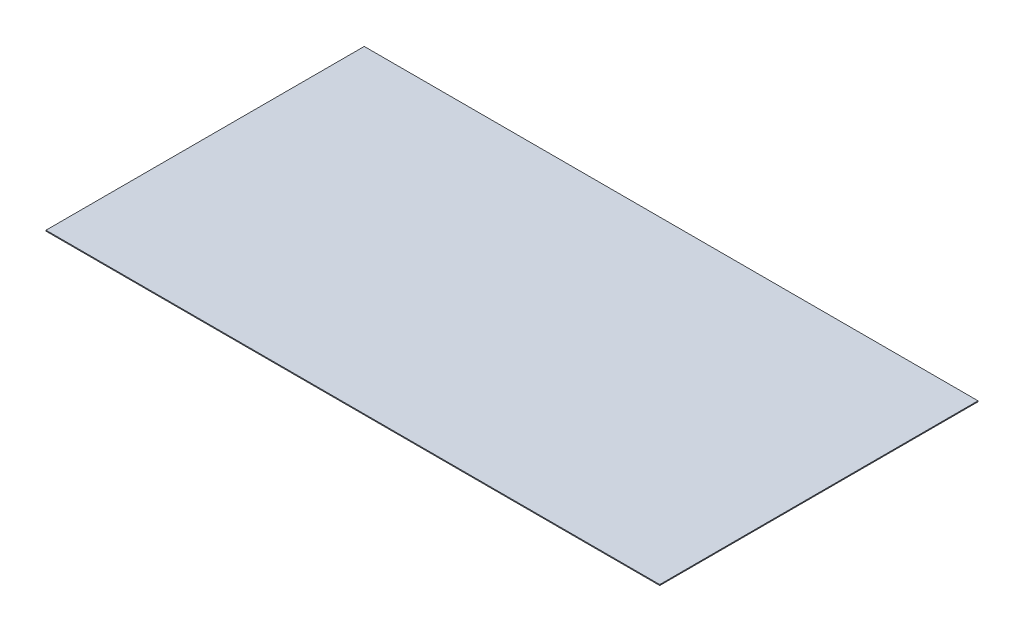
SolidWorks part; units mm, degrees
ref_plane "Спереди" through (0, 0, 0) normal (0, 0, 1) x (1, 0, 0)
ref_plane "Сверху" through (0, 0, 0) normal (0, 1, 0) x (1, 0, 0)
ref_plane "Справа" through (0, 0, 0) normal (1, 0, 0) x (0, 0, -1)
sketch "MASTER_FOOTPRINT" plane through (0, 0, 0) normal (0, 1, 0) x (1, 0, 0)
  line L1 (0, 0) -> (1350, 0)
  line L2 (0, 0) -> (0, 700)
  line L3 (0, 700) -> (1350, 700)
  line L4 (1350, 0) -> (1350, 700)
  dimension "D1" = 1350
  dimension "D2" = 700
extrude "BATH_BASE_PLATE" add sketch "MASTER_FOOTPRINT" along normal blind 2
equation "\"AI_Q_Peak\"= 0.006"
equation "\"AI_B_Bath\"= 700"
equation "\"AI_L_Settle\"= 900"
equation "\"AI_L_Inlet\"= 250"
equation "\"AI_L_Outlet\"= 200"
equation "\"AI_L_Bath\"= 1350"
equation "\"AI_H_Water\"= 550"
equation "\"AI_H_Freeboard\"= 200"
equation "\"AI_H_Bath\"= 750"
equation "\"AI_Shell_Thickness\"= 2"
equation "\"AI_Inlet_DN\"= 100"
equation "\"AI_Weir_Width\"= 600"
equation "\"AI_Inlet_Baffle_Offset\"= 125"
equation "\"AI_Distributor_Open_Area\"= 0.28"
equation "\"AI_Distributor_Hole_Dia\"= 22"
equation "\"AI_Distributor_Blind_Zone\"= 110"
equation "\"AI_Outlet_Baffle_Depth\"= 250"
equation "\"AI_Screw_Diameter\"= 100"
equation "\"AI_Screw_Pitch\"= 100"
equation "\"AI_Screw_Angle\"= 30"
equation "\"AI_Screw_Rpm\"= 15"
equation "\"AI_Screw_Clearance\"= 5"
equation "\"AI_Liner_Thickness\"= 5"
equation "\"AI_Discharge_Height\"= 650"
equation "\"AI_Frame_Height\"= 500"
equation "\"D1@MASTER_FOOTPRINT\" = \"AI_L_Bath\""
equation "\"D2@MASTER_FOOTPRINT\" = \"AI_B_Bath\""
